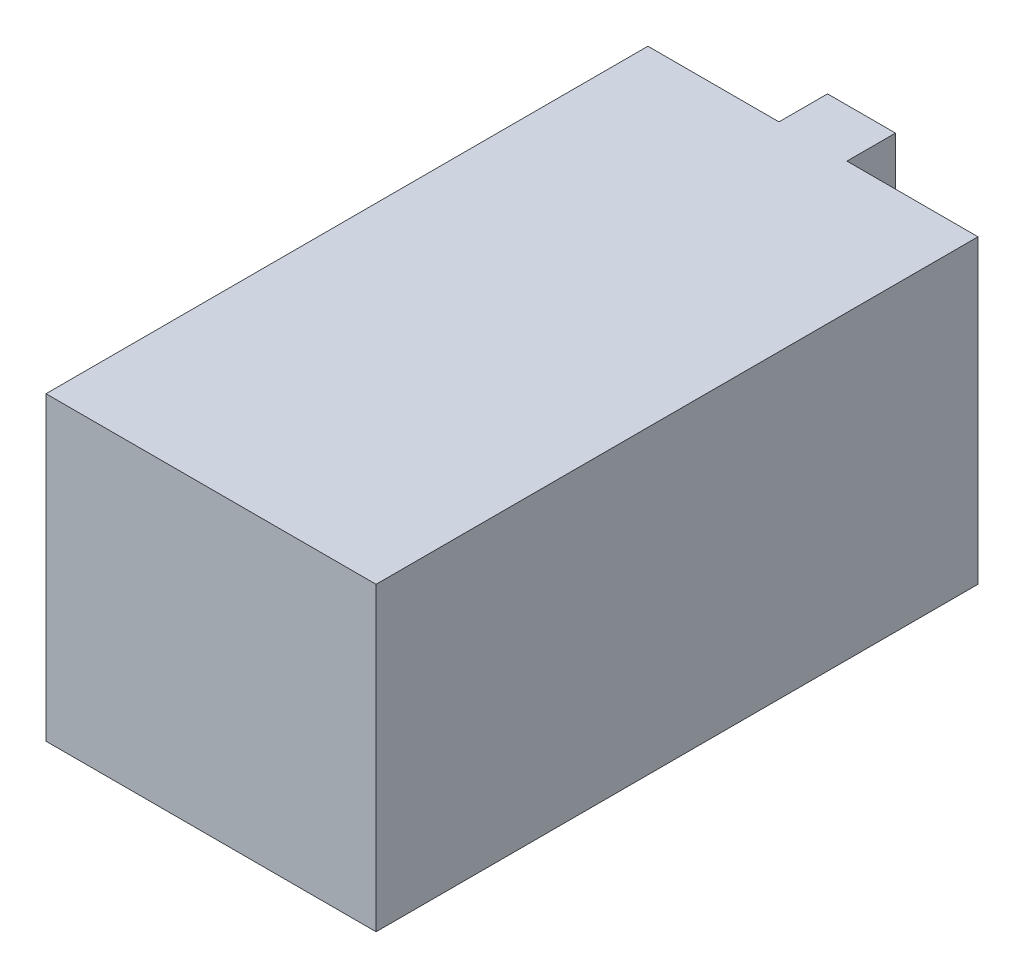
SolidWorks part; units mm, degrees
ref_plane "Front Plane" through (0, 0, 0) normal (0, 0, 1) x (1, 0, 0)
ref_plane "Top Plane" through (0, 0, 0) normal (0, 1, 0) x (1, 0, 0)
ref_plane "Right Plane" through (0, 0, 0) normal (1, 0, 0) x (0, 0, -1)
sketch "Sketch1" plane through (0, 0, 0) normal (0, 1, 0) x (1, 0, 0)
  line L1 (-17, 31) -> (17, 31)
  line L2 (-17, 31) -> (-17, -31)
  line L3 (-17, -31) -> (17, -31)
  line L4 (17, 31) -> (17, -31)
  line L5 (-17, 31) -> (17, -31) construction
  line L6 (-17, -31) -> (17, 31) construction
  line L7 (-3.5, 26) -> (3.5, 26)
  line L8 (-3.5, 26) -> (-3.5, 36)
  line L9 (-3.5, 36) -> (3.5, 36)
  line L10 (3.5, 26) -> (3.5, 36)
  line L11 (-3.5, 26) -> (3.5, 36) construction
  line L12 (-3.5, 36) -> (3.5, 26) construction
  point P0 (0, 0)
  point P6 (0, 31)
  dimension "D1" = 34
  dimension "D2" = 62
  dimension "D3" = 10
  dimension "D4" = 7
extrude "Boss-Extrude1" add sketch "Sketch1" along normal blind 31 contours L7 L10 L1 L8 | L1 L10 L9 L8 | L10 L7 L8 L1 L2 L3 L4
